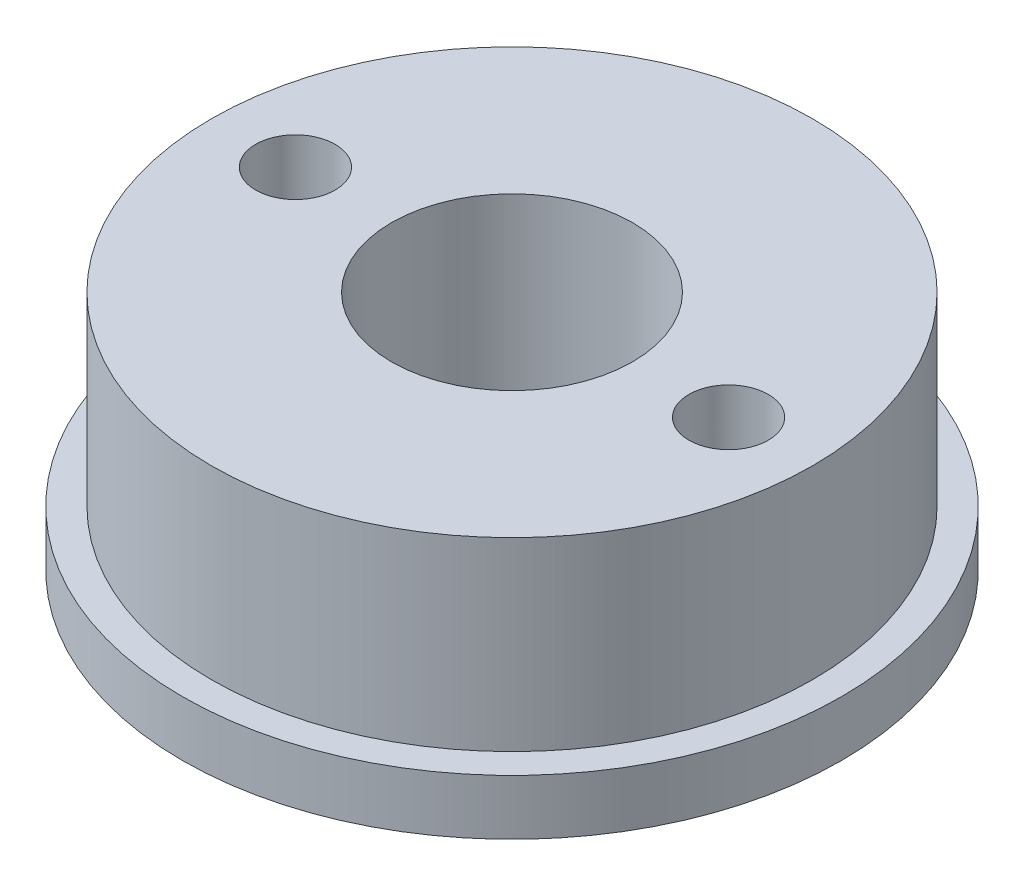
SolidWorks part; units mm, degrees
material "5052-H34"
ref_plane "正面" through (0, 0, 0) normal (0, 0, 1) x (1, 0, 0)
ref_plane "平面" through (0, 0, 0) normal (0, 1, 0) x (1, 0, 0)
ref_plane "右側面" through (0, 0, 0) normal (1, 0, 0) x (0, 0, -1)
sketch "ｽｹｯﾁ1" plane through (0, 0, 0) normal (0, 1, 0) x (1, 0, 0)
  circle A0 centre (0, 0) radius 13.7
  dimension "D1" = 27.4
extrude "ﾎﾞｽ - 押し出し1" add sketch "ｽｹｯﾁ1" along normal blind 2.3
sketch "ｽｹｯﾁ2" plane through (0, 2.3, 0) normal (0, 1, 0) x (1, 0, 0)
  circle A0 centre (0, 0) radius 12.49
  dimension "D1" = 24.98
extrude "ﾎﾞｽ - 押し出し2" add sketch "ｽｹｯﾁ2" along normal blind 7.7
sketch "ｽｹｯﾁ3" plane through (0, 0, 0) normal (0, -1, 0) x (1, 0, 0)
  line L0 (0, 13.7) -> (0, 0) construction
  line L1 (0, 0) -> (13.7, 0) construction
  circle A0 centre (0, 0) radius 5.01
  circle A1 centre (0, 0) radius 13.7 construction
  circle A2 centre (9, 0) radius 1.65
  circle A3 centre (-9, 0) radius 1.65
  dimension "D1" = 10.02
  dimension "D2" = 3.3
  dimension "D3" = 18
extrude "ｶｯﾄ - 押し出し1" cut sketch "ｽｹｯﾁ3" against normal up to surface (10 mm away) up to face at (0, 10, 12.49)
